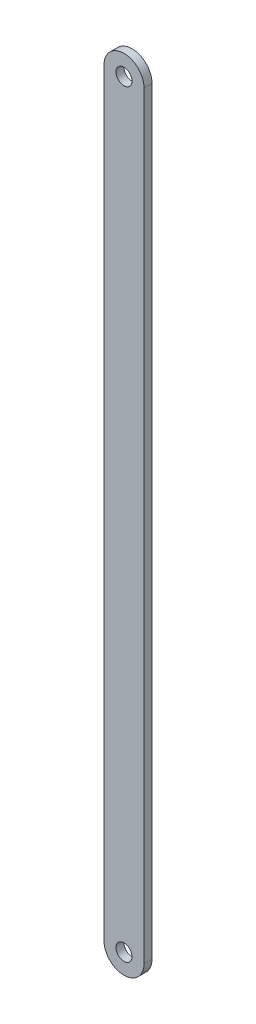
SolidWorks part; units mm, degrees
ref_plane "Alzado" through (0, 0, 0) normal (0, 0, 1) x (1, 0, 0)
ref_plane "Planta" through (0, 0, 0) normal (0, 1, 0) x (1, 0, 0)
ref_plane "Vista lateral" through (0, 0, 0) normal (1, 0, 0) x (0, 0, -1)
sketch "Croquis1" plane through (0, 0, 0) normal (0, 0, 1) x (1, 0, 0)
  line L0 (0, 0) -> (50, 0) construction
  line L1 (50, 0) -> (50, 945.2)
  line L2 (50, 945.2) -> (0, 945.2) construction
  line L3 (0, 945.2) -> (0, 0)
  arc A0 (0, 0) -> (50, 0) centre (25, 0) ccw
  arc A1 (50, 945.2) -> (0, 945.2) centre (25, 945.2) ccw
  circle A2 centre (25, 945.2) radius 10
  circle A3 centre (25, 0) radius 10
  dimension "D3" = 20
  dimension "D4" = 20
  dimension "D1" = 50
  dimension "D2" = 945.2
extrude "Saliente-Extruir1" add sketch "Croquis1" along normal blind 10
